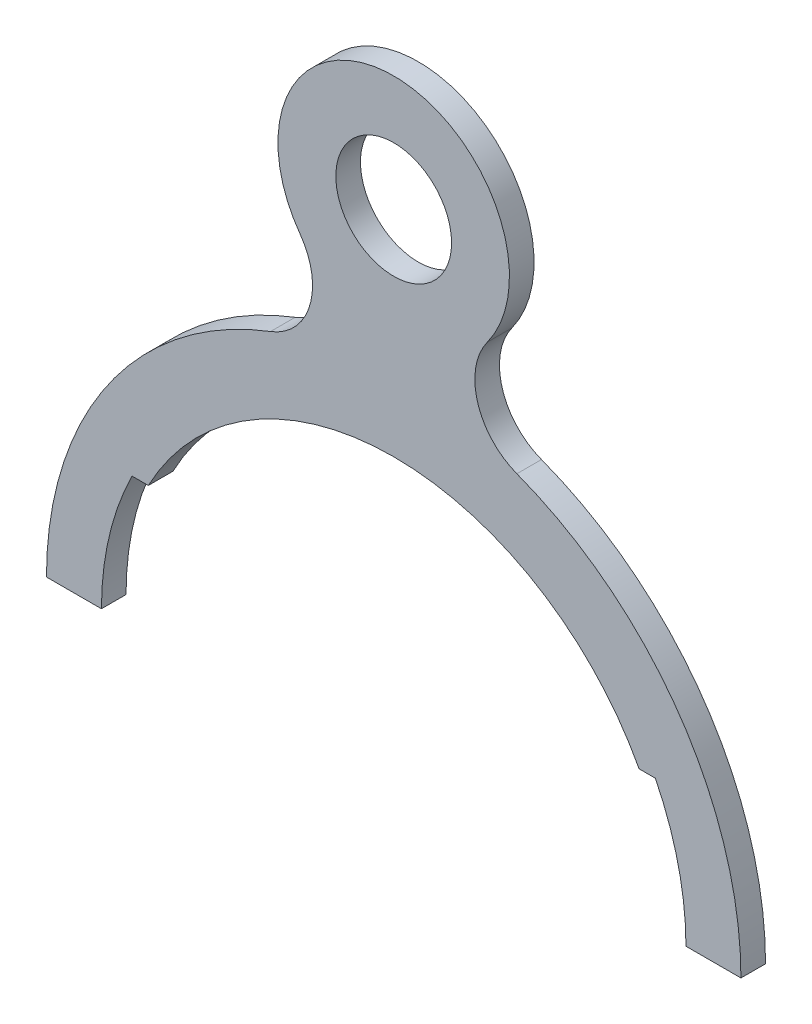
SolidWorks part; units mm, degrees
ref_plane "前视基准面" through (0, 0, 0) normal (0, 0, 1) x (1, 0, 0)
ref_plane "上视基准面" through (0, 0, 0) normal (0, 1, 0) x (1, 0, 0)
ref_plane "右视基准面" through (0, 0, 0) normal (1, 0, 0) x (0, 0, -1)
sketch "草图1" plane through (0, 0, 0) normal (0, 0, 1) x (1, 0, 0)
  line L0 (0, 0) -> (0, 283.494) construction
  line L1 (-40, 170) -> (-40, 169.7056)
  line L2 (40, 170) -> (40, 169.7056)
  line L3 (-90.4212, 45) -> (-84.7998, 45)
  line L4 (-120, 0) -> (-101, 0)
  line L5 (101, 0) -> (120, 0)
  line L6 (84.7998, 45) -> (90.4212, 45)
  arc A0 (84.7998, 45) -> (-84.7998, 45) centre (0, 0) ccw
  arc A1 (-40, 169.7056) -> (-76.3636, 92.5667) centre (-140, 169.7056) cw
  arc A2 (101, 0) -> (90.4212, 45) centre (0, 0) ccw
  arc A3 (120, 0) -> (76.3636, 92.5667) centre (0, 0) ccw
  arc A4 (-76.3636, 92.5667) -> (-120, 0) centre (0, 0) ccw
  circle A5 centre (0, 170) radius 20
  arc A6 (40, 170) -> (-40, 170) centre (0, 170) ccw
  arc A7 (76.3636, 92.5667) -> (40, 169.7056) centre (140, 169.7056) cw
  arc A8 (-90.4212, 45) -> (-101, 0) centre (0, 0) ccw
  dimension "D1" = 96
  dimension "D2" = 80
  dimension "D3" = 100
  dimension "D4" = 100
  dimension "D7" = 40
  dimension "D9" = 170
  dimension "D5" = 120
  dimension "D6" = 101
  dimension "D8" = 45
extrude "凸台-拉伸1" add sketch "草图1" along normal blind 8.5
hole_wizard "M4 螺纹孔1" positions "3D草图1" profile "草图3" tap size "M4" standard "ISO"
sketch3d "3D草图1"
  line L0 (-120, 0, 0) -> (-101, 0, 0) construction
  line L2 (101, 0, 0) -> (120, 0, 0) construction
  line L4 (-120, 0, 8.5) -> (-120, 0, 0) construction
  line L5 (120, 0, 8.5) -> (120, 0, 0) construction
  point P0 (-115, 0, 4.25)
  point P2 (115, 0, 4.25)
  dimension "D1" = 4.25
  dimension "D2" = 5
  dimension "D3" = 4.25
  dimension "D4" = 5
sketch "草图3" plane through (-115, 0, 4.25) normal (1, 0, 0) x (0, 0, -1)
  line L0 (0, 0) -> (0, 11.0914)
  line L1 (0, 11.0914) -> (1.65, 10.1)
  line L2 (1.65, 10.1) -> (1.65, 0)
  line L5 (1.65, 0) -> (0, 0)
  line L10 (0, 11.0914) -> (-1.65, 10.1) construction
  line L11 (0, -6.35) -> (0, 107.95) construction
  dimension "螺纹孔钻头直径" = 3.3
  dimension "螺纹孔钻头深度" = 10.1
  dimension "导头角度" = 118
cosmetic thread "孔螺蚊线1" parameters "D1"=8, "D2"=4
cosmetic thread "孔螺蚊线2" parameters "D1"=8, "D2"=4
sketch "草图4" plane through (0, 0, 8.5) normal (0, 0, 1) x (1, 0, 0)
  line L0 (-40, 170) -> (-40, 210)
  line L1 (-40, 210) -> (40, 210)
  line L2 (40, 210) -> (40, 170)
  line L3 (-40, 170) -> (0, 265.5704)
  line L4 (0, 265.5704) -> (40, 170)
  arc A0 (40, 170) -> (-40, 170) centre (0, 170) ccw construction
extrude "凸台-拉伸2" [suppressed] add sketch "草图4" against normal up to surface (8.5 mm away)
chamfer "倒角1" [suppressed] distance 30 angle 45
sketch "草图5" plane through (0, 0, 8.5) normal (0, 0, 1) x (1, 0, 0)
  line L0 (-40, 170) -> (-40, 169.7056) construction
  line L1 (-40, 170) -> (-40, 169.7056)
  arc A0 (-40, 170) -> (-32.3476, 146.4706) centre (0, 170) ccw
  arc A1 (40, 170) -> (-40, 170) centre (0, 170) ccw construction
  arc A2 (-42.5626, 112.1981) -> (-76.3636, 92.5667) centre (0, 0) ccw
  arc A3 (-76.3636, 92.5667) -> (-120, 0) centre (0, 0) ccw construction
  arc A4 (-42.5626, 112.1981) -> (-32.3476, 146.4706) centre (-50.5431, 133.2353) ccw
  arc A5 (-76.3636, 92.5667) -> (-40, 169.7056) centre (-140, 169.7056) ccw construction
  arc A6 (-76.3636, 92.5667) -> (-40, 169.7056) centre (-140, 169.7056) ccw
  dimension "D1" = 45
extrude "切除-拉伸1" cut sketch "草图5" against normal blind 10
mirror "镜向1" about plane through (0, 0, 0) normal (1, 0, 0) of "切除-拉伸1"
